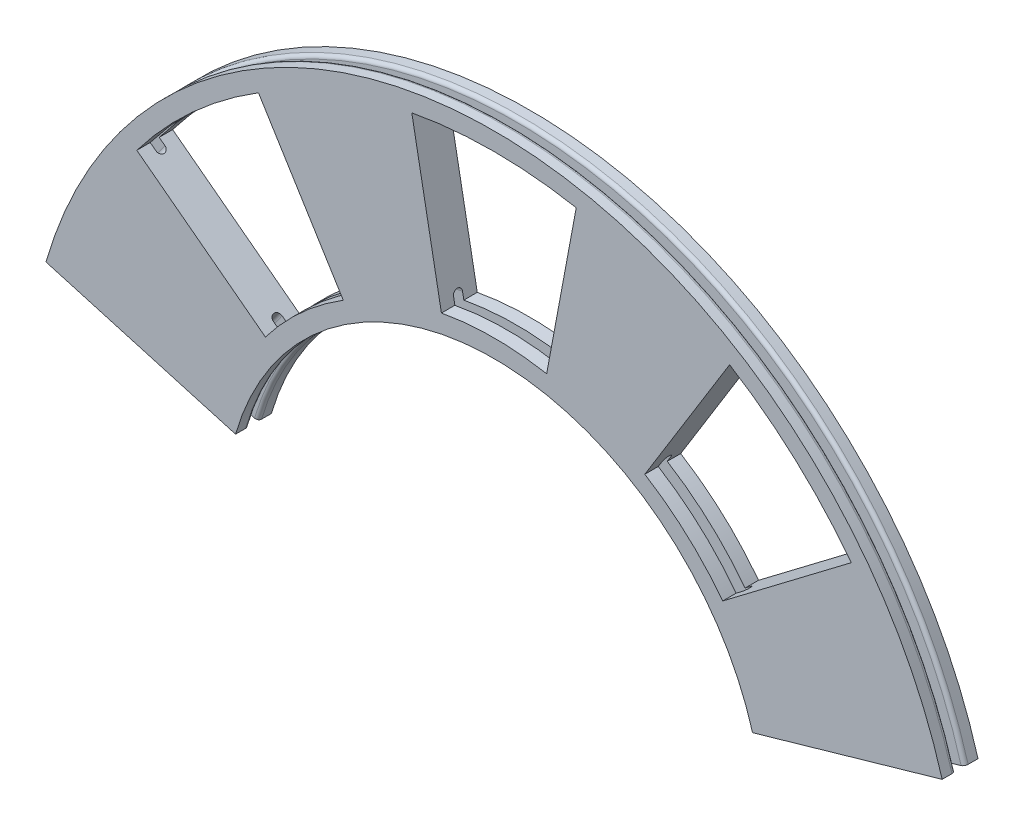
SolidWorks part; units mm, degrees
ref_plane "Front Plane" through (0, 0, 0) normal (0, 0, 1) x (1, 0, 0)
ref_plane "Top Plane" through (0, 0, 0) normal (0, 1, 0) x (1, 0, 0)
ref_plane "Right Plane" through (0, 0, 0) normal (1, 0, 0) x (0, 0, -1)
sketch "Sketch1" plane through (0, 0, 0) normal (0, 0, 1) x (1, 0, 0)
  line L0 (0, 0) -> (-124.964, 35.8329)
  line L1 (0, 0) -> (124.964, 35.8329)
  line L2 (0, 0) -> (0, 130) construction
  line L3 (0, 0) -> (-103.6272, 78.4946) construction
  line L4 (0, 0) -> (-68.3444, 110.585) construction
  line L5 (0, 0) -> (-23.8627, 127.7911) construction
  line L6 (0, 0) -> (23.8308, 127.7971) construction
  line L7 (0, 0) -> (68.3168, 110.602) construction
  line L8 (0, 0) -> (103.6077, 78.5204) construction
  line L9 (0, 0) -> (-103.6272, 78.4946) construction
  line L10 (0, 0) -> (-68.3444, 110.585) construction
  line L11 (-103.6272, 78.4946) -> (-59.7849, 45.2853)
  line L12 (-68.3444, 110.585) -> (-39.4295, 63.799)
  line L13 (-23.8627, 127.7911) -> (-13.7669, 73.7256)
  line L14 (23.8308, 127.7971) -> (13.7486, 73.7291)
  line L15 (68.3168, 110.602) -> (39.4136, 63.8089)
  line L16 (103.6077, 78.5204) -> (59.7736, 45.3002)
  arc A0 (72.0946, 20.6728) -> (-72.0946, 20.6728) centre (0, 0) ccw
  arc A1 (124.964, 35.8329) -> (-124.964, 35.8329) centre (0, 0) ccw
  arc A2 (76.9009, 22.051) -> (-76.9009, 22.051) centre (0, 0) ccw
  arc A3 (120.1577, 34.4547) -> (-120.1577, 34.4547) centre (0, 0) ccw
  dimension "D1" = 260
  dimension "D2" = 150
  dimension "D3" = 250
  dimension "D4" = 160
  dimension "D5" = 74
  dimension "D6" = 74
  dimension "D7" = 21.143
  dimension "D9" = 21.14
  dimension "D8" = 6
extrude "Boss-Extrude1" add sketch "Sketch1" along normal blind 10 contours L11 A3 L0 A2 | L13 A3 L12 A2 | L15 A3 L14 A2 | L1 A3 L16 A2 | L11 A2 L0 A0 | L12 A2 L11 A0 | L13 A2 L12 A0 | L14 A2 L13 A0 | L15 A2 L14 A0 | L16 A2 L15 A0 | L1 A2 L16 A0 | A3 L1 A1 L16 | A3 L16 A1 L15 | A3 L15 A1 L14 | A3 L14 A1 L13 | A3 L13 A1 L12 | A3 L12 A1 L11 | A3 L11 A1 L0
sketch "Sketch2" plane through (0, 0, 0) normal (0.2756, -0.9613, 0) x (0.9613, 0.2756, 0)
  line L0 (75, 5) -> (82, 5) construction
  line L1 (75, 10) -> (75, 0) construction
  line L2 (75, 6.25) -> (82, 6.25)
  line L3 (75, 3.75) -> (82, 3.75)
  line L4 (123, 5) -> (130, 5) construction
  line L5 (130, 10) -> (130, 0) construction
  line L6 (123, 6.25) -> (130, 6.25)
  line L7 (123, 3.75) -> (130, 3.75)
  arc A0 (75, 6.25) -> (75, 3.75) centre (75, 5) ccw
  arc A1 (82, 3.75) -> (82, 6.25) centre (82, 5) ccw
  arc A2 (123, 6.25) -> (123, 3.75) centre (123, 5) ccw
  arc A3 (130, 3.75) -> (130, 6.25) centre (130, 5) ccw
  point P4 (78.5, 5)
  point P9 (126.5, 5)
  dimension "D2" = 1.25
  dimension "D4" = 1.25
  dimension "D1" = 7
  dimension "D3" = 7
sketch "Sketch3" plane through (0, 0, 10) normal (0, 0, 1) x (1, 0, 0)
  circle A0 centre (0, 0) radius 75
  dimension "D1" = 150
sweep "Cut-Sweep1" cut profiles "Sketch2" path "Sketch3"
fillet "Fillet1" radius 1 4 edges at (0, 130, 6.25) (0, 130, 3.75) (0, 75, 6.25) (0, 75, 3.75)
equation "\"D6@Sketch1\"=\"D5@Sketch1\""
equation "\"D7@Sketch1\"=(\"D5@Sketch1\"+\"D6@Sketch1\")/7"
equation "\"D3@Sketch2\"=\"D1@Sketch2\""
equation "\"D4@Sketch2\"=\"D2@Sketch2\""
